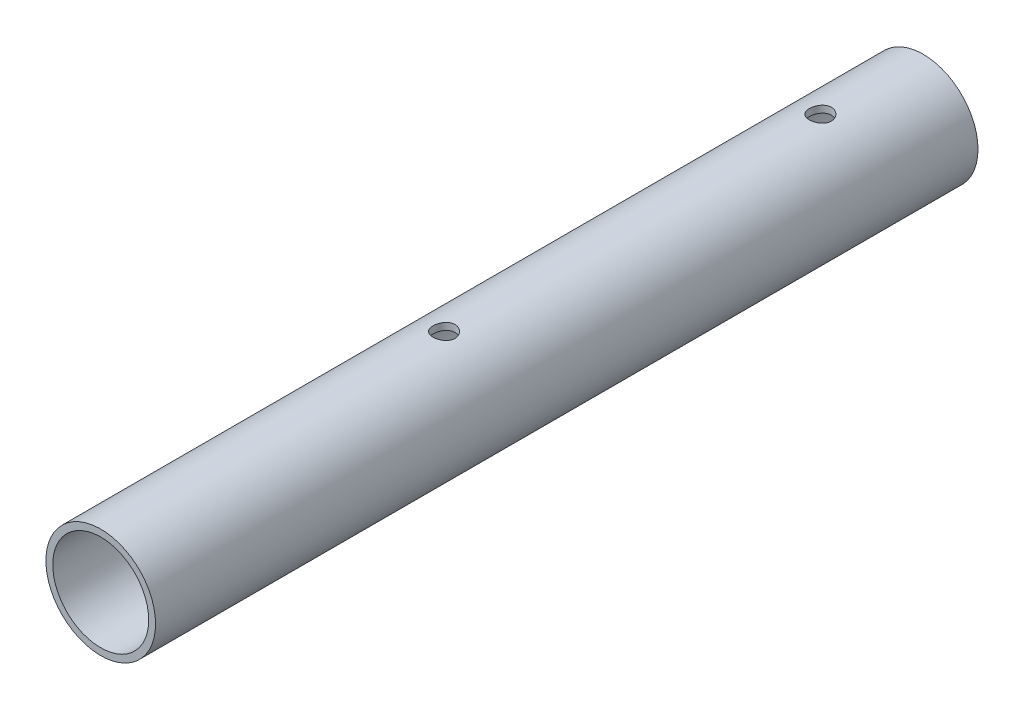
SolidWorks part; units mm, degrees
material "Thornel Mat VMA"
ref_plane "前视基准面" through (0, 0, 0) normal (0, 0, 1) x (1, 0, 0)
ref_plane "上视基准面" through (0, 0, 0) normal (0, 1, 0) x (1, 0, 0)
ref_plane "右视基准面" through (0, 0, 0) normal (1, 0, 0) x (0, 0, -1)
other "Configuration Table"
sketch "草图1" plane through (0, 0, 0) normal (0, 0, 1) x (1, 0, 0)
  circle A0 centre (0, 0) radius 8
  circle A1 centre (0, 0) radius 7
  dimension "D1" = 14
  dimension "D2" = 16
extrude "凸台-拉伸1" add sketch "草图1" along normal blind 120
sketch "草图2" plane through (0, 0, 0) normal (0, 1, 0) x (1, 0, 0)
  line L0 (0, 0) -> (0, -15) construction
  line L1 (0, -15) -> (0, -69.91) construction
  circle A0 centre (0, -15) radius 1.6
  circle A1 centre (0, -69.91) radius 1.6
  dimension "D2" = 3.2
  dimension "D4" = 3.2
  dimension "D1" = 15
  dimension "D3" = 54.91
extrude "切除-拉伸1" cut sketch "草图2" against normal mid plane 600
